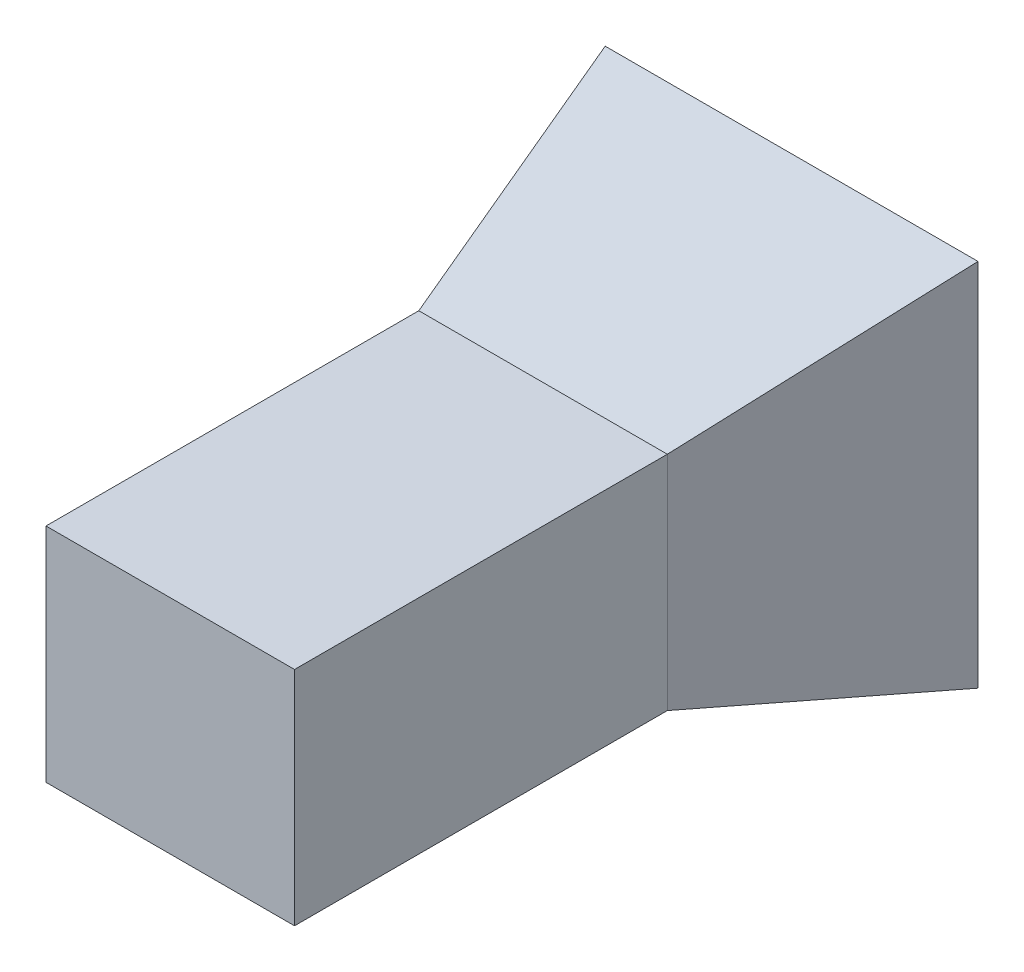
SolidWorks part; units mm, degrees
ref_plane "Front Plane" through (0, 0, 0) normal (0, 0, 1) x (1, 0, 0)
ref_plane "Top Plane" through (0, 0, 0) normal (0, 1, 0) x (1, 0, 0)
ref_plane "Right Plane" through (0, 0, 0) normal (1, 0, 0) x (0, 0, -1)
sketch "Sketch1" plane through (0, 0, 0) normal (0, 0, 1) x (1, 0, 0)
  line L1 (-15, 14.8707) -> (15, 14.8707)
  line L2 (-15, 14.8707) -> (-15, -14.8707)
  line L3 (-15, -14.8707) -> (15, -14.8707)
  line L4 (15, 14.8707) -> (15, -14.8707)
  line L5 (-15, 14.8707) -> (15, -14.8707) construction
  line L6 (-15, -14.8707) -> (15, 14.8707) construction
  point P0 (0, 0)
  dimension "D1" = 30
ref_plane "Plane1" through (0, 0, 20) normal (0, 0, 1) x (1, 0, 0)
sketch "Sketch2" plane through (0, 0, 20) normal (0, 0, 1) x (1, 0, 0)
  line L1 (-10, 8.9331) -> (10, 8.9331)
  line L2 (-10, 8.9331) -> (-10, -8.9331)
  line L3 (-10, -8.9331) -> (10, -8.9331)
  line L4 (10, 8.9331) -> (10, -8.9331)
  line L5 (-10, 8.9331) -> (10, -8.9331) construction
  line L6 (-10, -8.9331) -> (10, 8.9331) construction
  point P0 (0, 0)
  dimension "D1" = 20
loft "Loft1" add profiles "Sketch1", "Sketch2"
sketch "Sketch3" plane through (0, 0, 20) normal (0, 0, 1) x (1, 0, 0)
  line L4 (10, -8.9331) -> (10, 8.9331)
  line L5 (10, 8.9331) -> (-10, 8.9331)
  line L6 (-10, 8.9331) -> (-10, -8.9331)
  line L7 (-10, -8.9331) -> (10, -8.9331)
  line L8 (10, -8.9331) -> (10, 8.9331)
  line L9 (10, 8.9331) -> (-10, 8.9331)
  line L10 (-10, 8.9331) -> (-10, -8.9331)
  line L11 (-10, -8.9331) -> (10, -8.9331)
  dimension "D1" = 0
extrude "Boss-Extrude1" add sketch "Sketch3" along normal blind 30
